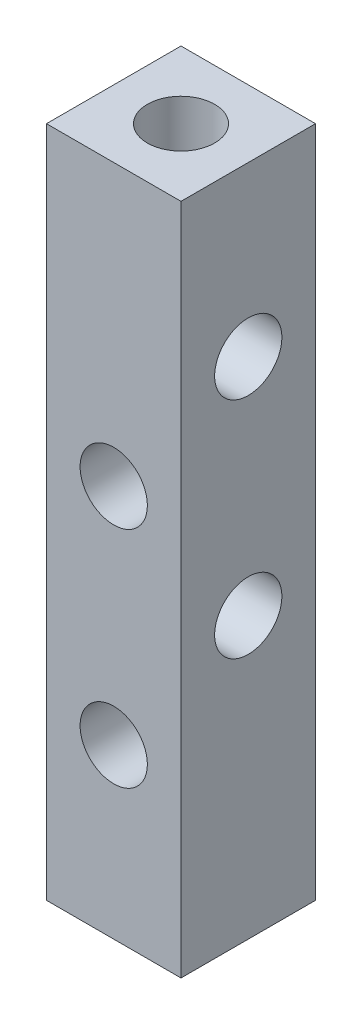
SolidWorks part; units mm, degrees
ref_plane "前视基准面" through (0, 0, 0) normal (0, 0, 1) x (1, 0, 0)
ref_plane "上视基准面" through (0, 0, 0) normal (0, 1, 0) x (1, 0, 0)
ref_plane "右视基准面" through (0, 0, 0) normal (1, 0, 0) x (0, 0, -1)
sketch "草图1" plane through (0, 0, 0) normal (0, 1, 0) x (1, 0, 0)
  line L1 (-3, -3) -> (3, -3)
  line L2 (-3, -3) -> (-3, 3)
  line L3 (-3, 3) -> (3, 3)
  line L4 (3, -3) -> (3, 3)
  line L5 (-3, -3) -> (3, 3) construction
  line L6 (-3, 3) -> (3, -3) construction
  point P0 (0, 0)
  dimension "D1" = 6
  dimension "D2" = 6
extrude "凸台-拉伸1" add sketch "草图1" along normal blind 30
sketch "草图2" plane through (0, 0, 3) normal (0, 0, 1) x (1, 0, 0)
  line L0 (-3, 30) -> (3, 30) construction
  line L1 (-3, 0) -> (3, 0) construction
  circle A0 centre (0, 17.5) radius 1.5
  circle A1 centre (0, 7.5) radius 1.5
  dimension "D1" = 3
  dimension "D2" = 12.5
  dimension "D3" = 3
  dimension "D4" = 7.5
extrude "切除-拉伸1" cut sketch "草图2" against normal up to next
sketch "草图3" plane through (3, 0, 0) normal (1, 0, 0) x (0, 0, -1)
  line L0 (-3, 30) -> (3, 30) construction
  line L1 (-3, 0) -> (3, 0) construction
  circle A0 centre (0, 22.5) radius 1.5
  circle A1 centre (0, 12.5) radius 1.5
  dimension "D1" = 3
  dimension "D2" = 7.5
  dimension "D3" = 3
  dimension "D4" = 12.5
extrude "切除-拉伸2" cut sketch "草图3" against normal up to next
sketch "草图4" plane through (0, 30, 0) normal (0, 1, 0) x (1, 0, 0)
  circle A0 centre (0, 0) radius 1.5
  dimension "D1" = 3
extrude "切除-拉伸3" cut sketch "草图4" against normal blind 5
sketch "草图5" plane through (0, 0, 0) normal (0, -1, 0) x (1, 0, 0)
  circle A0 centre (0, 0) radius 1.5
  dimension "D1" = 3
extrude "切除-拉伸4" cut sketch "草图5" against normal blind 5
